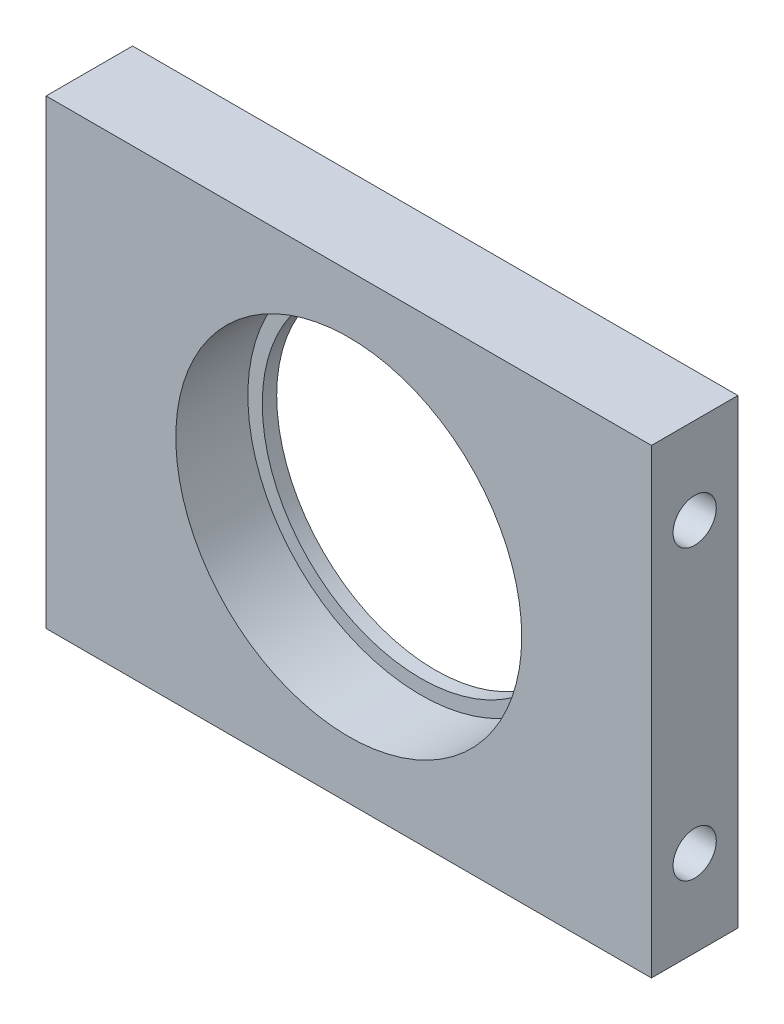
SolidWorks part; units mm, degrees
ref_plane "前视基准面" through (0, 0, 0) normal (0, 0, 1) x (1, 0, 0)
ref_plane "上视基准面" through (0, 0, 0) normal (0, 1, 0) x (1, 0, 0)
ref_plane "右视基准面" through (0, 0, 0) normal (1, 0, 0) x (0, 0, -1)
ref_plane "基准面1" through (0, 0, 6) normal (0, 0, 1) x (1, 0, 0)
sketch "草图1" plane through (0, 0, 6) normal (0, 0, 1) x (1, 0, 0)
  line L0 (-21, 16) -> (-21, -16)
  line L1 (-21, -16) -> (21, -16)
  line L2 (21, -16) -> (21, 16)
  line L3 (21, 16) -> (-21, 16)
extrude "凸台-拉伸1" add sketch "草图1" against normal blind 6
hole_wizard "Ø3.0 (3) 直径孔1" positions "草图3" profile "草图2" hole size "Ø3.0" standard "ANSI Metric"
sketch "草图3" plane through (21, 0, 0) normal (1, 0, 0) x (0, 0, -1)
  point P0 (-3, -10)
  point P1 (-3, 10)
sketch "草图2" plane through (21, -10, 3) normal (0, 1, 0) x (0, 0, -1)
  line L0 (0, 0) -> (0, 6)
  line L1 (0, 6) -> (1.5, 6)
  line L2 (1.5, 6) -> (1.5, 0)
  line L5 (1.5, 0) -> (0, 0)
  line L10 (0, 6) -> (-1.5, 6) construction
  line L11 (0, -6.35) -> (0, 107.95) construction
  dimension "孔直径" = 3
  dimension "孔深度" = 6
  dimension "导头角度" = 180
hole_wizard "Ø3.0 (3) 直径孔2" positions "草图5" profile "草图4" hole size "Ø3.0" standard "ANSI Metric"
sketch "草图5" plane through (-21, 0, 0) normal (-1, 0, 0) x (0, 0, 1)
  point P0 (3, -10)
  point P1 (3, 10)
sketch "草图4" plane through (-21, -10, 3) normal (0, 1, 0) x (0, 0, 1)
  line L0 (0, 0) -> (0, 6)
  line L1 (0, 6) -> (1.5, 6)
  line L2 (1.5, 6) -> (1.5, 0)
  line L5 (1.5, 0) -> (0, 0)
  line L10 (0, 6) -> (-1.5, 6) construction
  line L11 (0, -6.35) -> (0, 107.95) construction
  dimension "孔直径" = 3
  dimension "孔深度" = 6
  dimension "导头角度" = 180
hole_wizard "M24x2.0 螺纹孔1" positions "草图7" profile "草图6" tap size "M24x2.0" standard "ANSI Metric"
sketch "草图7" plane through (0, 0, 6) normal (0, 0, 1) x (1, 0, 0)
  point P0 (0, 0)
sketch "草图6" plane through (0, 0, 6) normal (1, 0, 0) x (0, -1, 0)
  line L0 (0, 0) -> (0, 6)
  line L1 (0, 6) -> (11, 6)
  line L3 (11, 6) -> (11, 4)
  line L4 (11, 4) -> (12, 4)
  line L5 (12, 4) -> (12, 0)
  line L7 (12, 0) -> (0, 0)
  line L11 (0, -6.35) -> (0, 107.95) construction
  dimension "通孔螺纹孔钻头直径" = 22
  dimension "通孔螺纹孔钻头深度" = 6
  dimension "螺纹线主直径" = 24
  dimension "螺纹线深度" = 4
sketch "草图8" plane through (0, 0, 6) normal (0, 0, 1) x (1, 0, 0)
  circle A0 centre (0, 0) radius 12
extrude "切除-拉伸1" cut sketch "草图8" against normal blind 5
